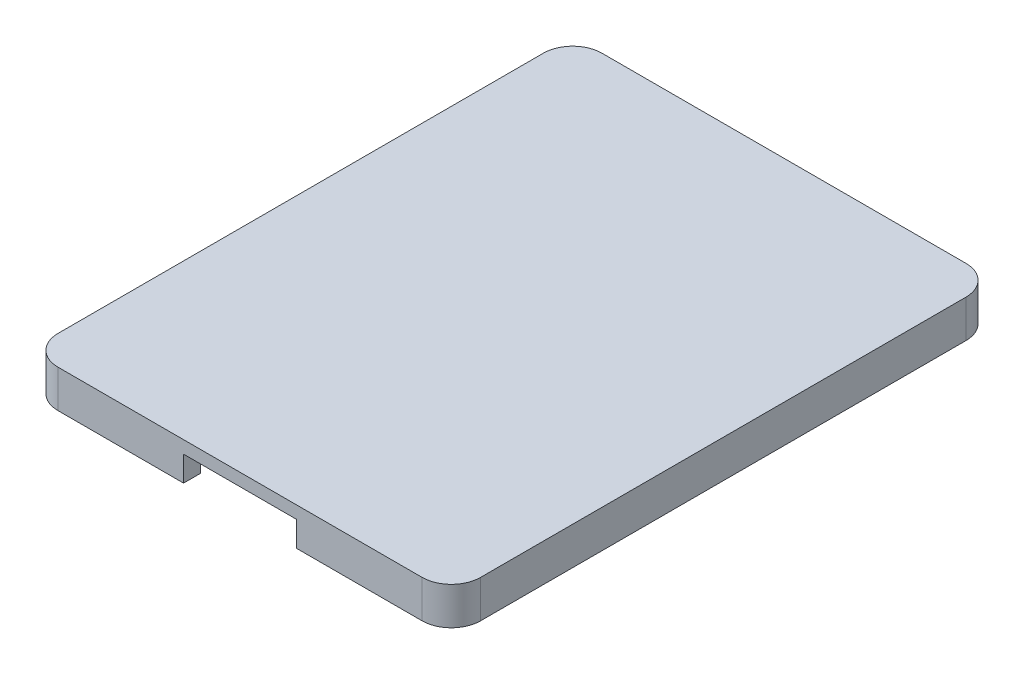
SolidWorks part; units mm, degrees
ref_plane "Alzado" through (0, 0, 0) normal (0, 0, 1) x (1, 0, 0)
ref_plane "Planta" through (0, 0, 0) normal (0, 1, 0) x (1, 0, 0)
ref_plane "Vista lateral" through (0, 0, 0) normal (1, 0, 0) x (0, 0, -1)
sketch "Sketch1" plane through (0, 0, 0) normal (0, 1, 0) x (1, 0, 0)
  line L1 (-21.75, -32.5) -> (21.75, -32.5)
  line L2 (-25.25, -29) -> (-25.25, 29)
  line L3 (-21.75, 32.5) -> (21.75, 32.5)
  line L4 (25.25, -29) -> (25.25, 29)
  line L5 (-25.25, -32.5) -> (25.25, 32.5) construction
  line L6 (-25.25, 32.5) -> (25.25, -32.5) construction
  arc A0 (-21.75, -32.5) -> (-25.25, -29) centre (-21.75, -29) cw
  arc A1 (21.75, -32.5) -> (25.25, -29) centre (21.75, -29) ccw
  arc A2 (-25.25, 29) -> (-21.75, 32.5) centre (-21.75, 29) cw
  arc A3 (21.75, 32.5) -> (25.25, 29) centre (21.75, 29) cw
  point P0 (0, 0)
  dimension "D3" = 3.5
  dimension "D1" = 50.5
  dimension "D2" = 65
extrude "Boss-Extrude1" add sketch "Sketch1" along normal blind 4.5
sketch "Sketch2" plane through (0, 0, 0) normal (0, -1, 0) x (1, 0, 0)
  line L0 (25.25, 29) -> (25.25, -29) construction
  line L1 (-19.75, -30.5) -> (19.75, -30.5)
  line L2 (-23.25, -27) -> (-23.25, 27)
  line L3 (-19.75, 30.5) -> (19.75, 30.5)
  line L4 (23.25, -27) -> (23.25, 27)
  line L5 (-23.25, -30.5) -> (23.25, 30.5) construction
  line L6 (-23.25, 30.5) -> (23.25, -30.5) construction
  line L7 (-21.75, 32.5) -> (21.75, 32.5) construction
  arc A0 (19.75, -30.5) -> (23.25, -27) centre (19.75, -27) ccw
  arc A1 (-19.75, -30.5) -> (-23.25, -27) centre (-19.75, -27) cw
  arc A2 (-23.25, 27) -> (-19.75, 30.5) centre (-19.75, 27) cw
  arc A3 (19.75, 30.5) -> (23.25, 27) centre (19.75, 27) cw
  point P0 (0, 0)
  dimension "D3" = 3.5
  dimension "D1" = 2
  dimension "D2" = 2
extrude "Cut-Extrude1" cut sketch "Sketch2" against normal blind 4
sketch "Sketch3" plane through (0, 0, 32.5) normal (0, 0, 1) x (1, 0, 0)
  line L0 (0, 0) -> (0, 4.5) construction
  line L1 (-21.75, 4.5) -> (21.75, 4.5) construction
  line L3 (-6.75, 3) -> (6.75, 3)
  line L4 (-6.75, 3) -> (-6.75, -3)
  line L5 (-6.75, -3) -> (6.75, -3)
  line L6 (6.75, 3) -> (6.75, -3)
  line L7 (-6.75, 3) -> (6.75, -3) construction
  line L8 (-6.75, -3) -> (6.75, 3) construction
  dimension "D1" = 1.5
  dimension "D2" = 13.5
extrude "Cut-Extrude2" cut sketch "Sketch3" against normal blind 15
